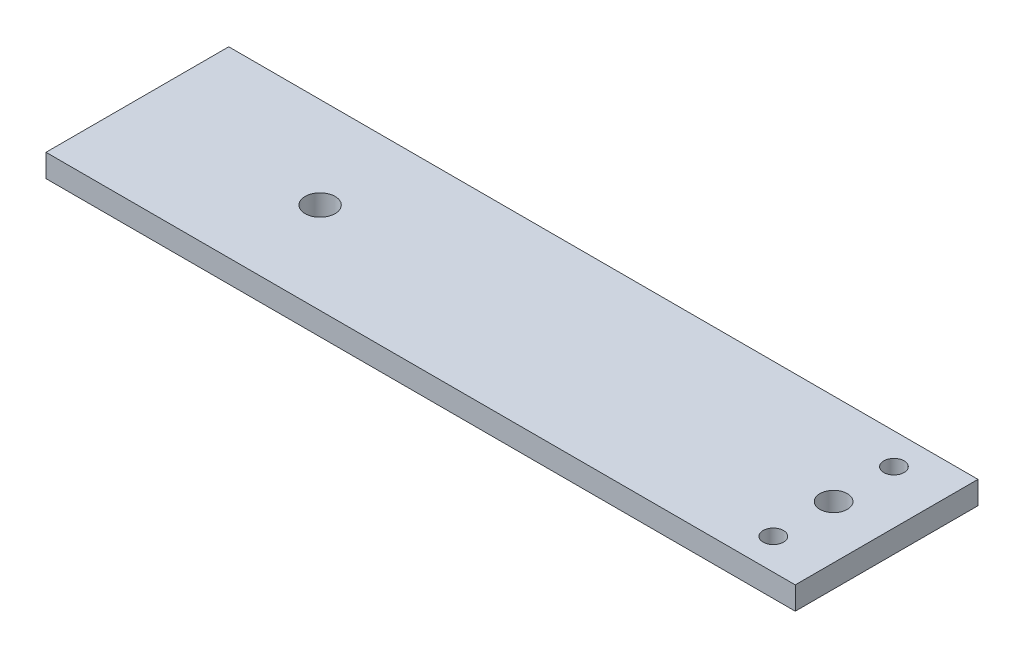
SolidWorks part; units mm, degrees
ref_plane "Front Plane" through (0, 0, 0) normal (0, 0, 1) x (1, 0, 0)
ref_plane "Top Plane" through (0, 0, 0) normal (0, 1, 0) x (1, 0, 0)
ref_plane "Right Plane" through (0, 0, 0) normal (1, 0, 0) x (0, 0, -1)
sketch "Sketch2" plane through (0, 0, 0) normal (0, 1, 0) x (1, 0, 0)
  line L0 (0, 12.7) -> (96.774, 12.7)
  line L1 (0, 0) -> (104.14, 0)
  line L2 (0, 0) -> (0, 25.4)
  line L3 (0, 25.4) -> (104.14, 25.4)
  line L4 (104.14, 0) -> (104.14, 25.4)
  line L5 (96.774, 12.7) -> (96.774, 21.082)
  line L6 (96.774, 12.7) -> (96.774, 4.318)
  circle A0 centre (96.774, 21.082) radius 1.4122
  circle A1 centre (96.774, 4.318) radius 1.4122
  circle A2 centre (96.774, 12.7) radius 1.905
  dimension "D1" = 104.14
  dimension "D2" = 25.4
  dimension "D3" = 96.774
extrude "Boss-Extrude1" add sketch "Sketch2" along normal blind 3.175
sketch "Sketch3" plane through (0, 3.175, 0) normal (0, 1, 0) x (1, 0, 0)
  line L0 (0, 25.4) -> (0, 12.7)
  line L1 (0, 25.4) -> (104.14, 25.4) construction
  line L2 (0, 0) -> (0, 25.4) construction
  line L3 (0, 12.7) -> (25.4, 12.7)
  circle A1 centre (25.4, 12.7) radius 2.0828
extrude "Cut-Extrude1" cut sketch "Sketch3" against normal blind 6.35
